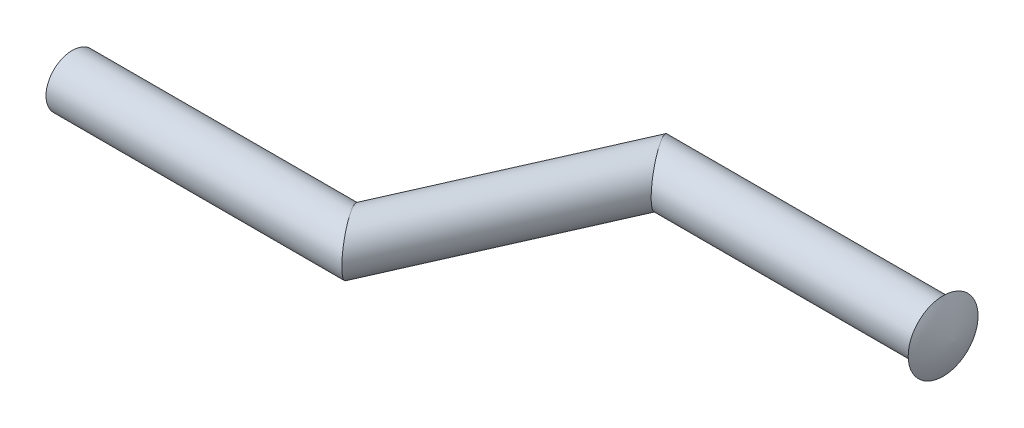
SolidWorks part; units mm, degrees
ref_plane "Front Plane" through (0, 0, 0) normal (0, 0, 1) x (1, 0, 0)
ref_plane "Top Plane" through (0, 0, 0) normal (0, 1, 0) x (1, 0, 0)
ref_plane "Right Plane" through (0, 0, 0) normal (1, 0, 0) x (0, 0, -1)
sketch "Sketch1" plane through (0, 0, 0) normal (0, 1, 0) x (1, 0, 0)
  line L0 (0, 0) -> (-95.9849, 0)
  line L1 (-95.9849, 0) -> (-128.2526, -72.7462)
  line L2 (-128.2526, -72.7462) -> (-222.8823, -72.7462)
sketch "Sketch3" plane through (0, 0, 0) normal (1, 0, 0) x (0, 0, -1)
  circle A0 centre (0, 0) radius 8.89
  dimension "D1" = 17.78
sweep "Sweep1" add profiles "Sketch3" path "Sketch1"
sketch "Sketch6" plane through (0, 0, 0) normal (0, 1, 0) x (1, 0, 0)
  line L0 (0, 0) -> (15.434, 0) construction
  line L1 (0, 0) -> (0, 11.8605)
  line L2 (0, 0) -> (3.407, 0)
  arc A0 (0, 11.8605) -> (3.407, 0) centre (-27.0941, -2.342) cw
revolve "Revolve1" add sketch "Sketch6" angle 360 about L0
